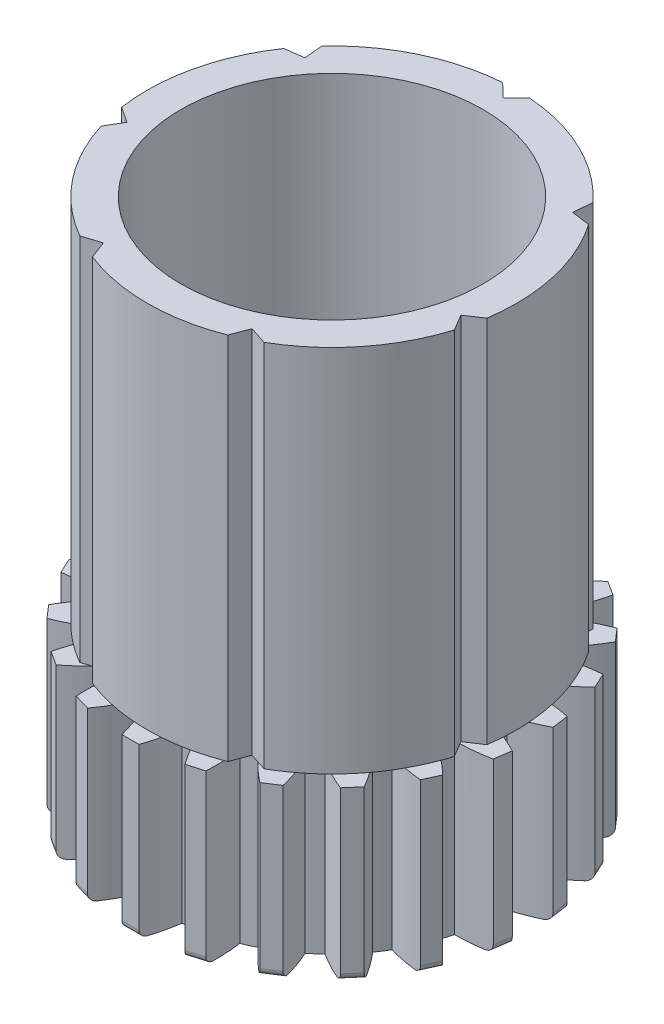
SolidWorks part; units mm, degrees
ref_plane "前视基准面" through (0, 0, 0) normal (0, 0, 1) x (1, 0, 0)
ref_plane "上视基准面" through (0, 0, 0) normal (0, 1, 0) x (1, 0, 0)
ref_plane "右视基准面" through (0, 0, 0) normal (1, 0, 0) x (0, 0, -1)
sketch "草图1" plane through (0, 0, 0) normal (0, 1, 0) x (1, 0, 0)
  circle A0 centre (0, 0) radius 5
  dimension "D1" = 10
extrude "凸台-拉伸1" add sketch "草图1" along normal blind 5
sketch "草图2" plane through (0, 0, 0) normal (0, -1, 0) x (1, 0, 0)
  line L0 (0, 0) -> (0, 5) construction
  line L1 (0, 5) -> (0, 6) construction
  line L2 (0, 5) -> (-0.5, 5) construction
  line L3 (0, 5.5) -> (-0.4, 5.5) construction
  line L4 (0.25, 6) -> (-0.25, 6)
  arc A0 (0.5038, 4.9746) -> (-0.5038, 4.9746) centre (0, 0) ccw
  arc A1 (-0.25, 6) -> (-0.5038, 4.9746) centre (4.925, 4.175) ccw
  arc A2 (0.25, 6) -> (0.5038, 4.9746) centre (-4.925, 4.175) cw
  dimension "D1" = 5
  dimension "D2" = 1
  dimension "D3" = 0.5
  dimension "D4" = 0.4
  dimension "D5" = 0.25
extrude "凸台-拉伸2" add sketch "草图2" against normal blind 5
fillet "圆角1" radius 0.2 1 edges at (0, 0, 6)
pattern_circular "阵列(圆周)2" count 22 over 360 about axis through (0, 0, 0) along (0, 1, 0) of "圆角1", "凸台-拉伸2"
sketch "草图3" plane through (0, 5, 0) normal (0, 1, 0) x (1, 0, 0)
  circle A0 centre (0, 0) radius 5.5
  dimension "D1" = 11
extrude "凸台-拉伸3" add sketch "草图3" along normal blind 11
sketch "草图4" plane through (0, 0, 0) normal (1, 0, 0) x (0, 0, -1)
  line L0 (0, 16) -> (-4.5, 16)
  line L1 (5.5, 16) -> (-5.5, 16) construction
  line L2 (-4.5, 16) -> (-4.5, 9)
  line L3 (0, 0) -> (-3, 0)
  line L4 (-0.2093, 0) -> (0.2093, 0) construction
  line L6 (-2.1217, 0) -> (-1.6082, 0) construction
  line L7 (-4.5, 9) -> (-3, 0)
  line L8 (0, 16) -> (0, 0)
  dimension "D1" = 4.5
  dimension "D2" = 7
  dimension "D3" = 3
revolve "切除-旋转1" cut sketch "草图4" angle 360 about L8
sketch "草图5" plane through (0, 16, 0) normal (0, 1, 0) x (1, 0, 0)
  line L0 (0, 0) -> (0, 5.5) construction
  line L1 (0, 5.5) -> (0, 5.1) construction
  line L2 (0.4037, 5.4852) -> (-0.4037, 5.4852) construction
  line L3 (-0.4037, 5.4852) -> (0, 5.1)
  line L4 (0.4037, 5.4852) -> (0, 5.1)
  arc A0 (0.4037, 5.4852) -> (-0.4037, 5.4852) centre (0, 0) ccw
  dimension "D2" = 0.4
extrude "切除-拉伸1" cut sketch "草图5" against normal blind 11
pattern_circular "阵列(圆周)3" count 7 over 360 about axis through (0, 0, 0) along (0, 1, 0) of "切除-拉伸1"
